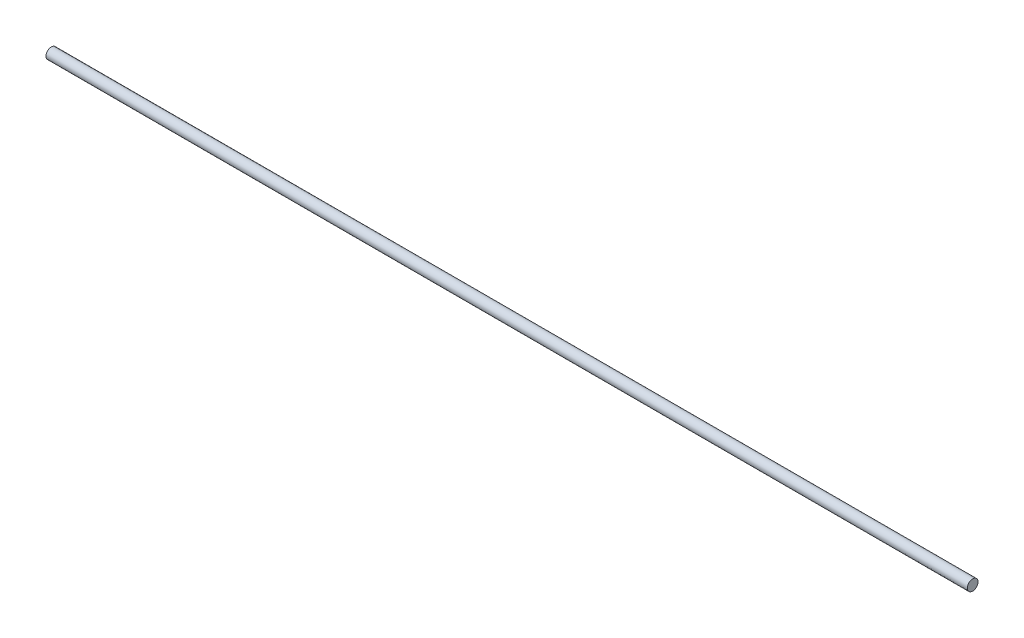
SolidWorks part; units mm, degrees
ref_plane "前视基准面" through (0, 0, 0) normal (0, 0, 1) x (1, 0, 0)
ref_plane "上视基准面" through (0, 0, 0) normal (0, 1, 0) x (1, 0, 0)
ref_plane "右视基准面" through (0, 0, 0) normal (1, 0, 0) x (0, 0, -1)
sketch "草图1" plane through (0, 0, 0) normal (1, 0, 0) x (0, 0, -1)
  circle A0 centre (0, 0) radius 2.5
  dimension "D1" = 5
extrude "凸台-拉伸1" add sketch "草图1" along normal blind 431.8
